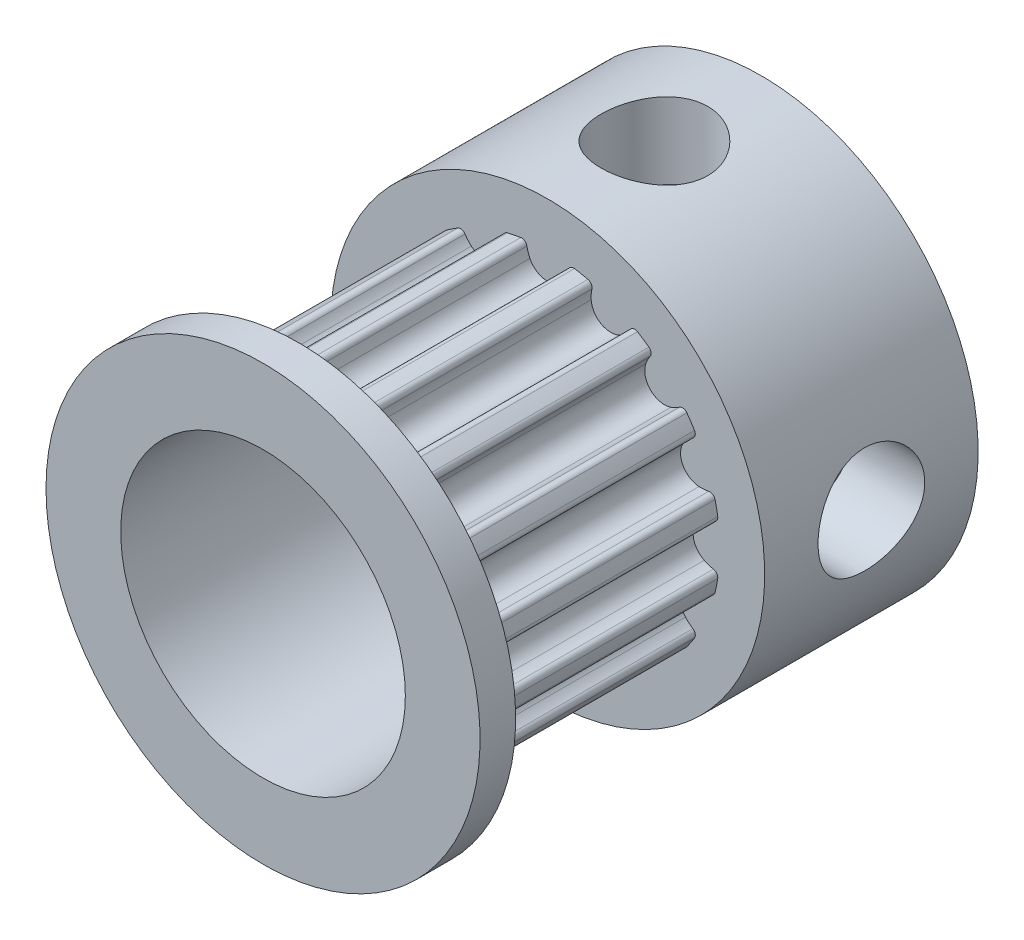
SolidWorks part; units mm, degrees
material "6061 Alloy"
ref_plane "Front Plane" through (0, 0, 0) normal (0, 0, 1) x (1, 0, 0)
ref_plane "Top Plane" through (0, 0, 0) normal (0, 1, 0) x (1, 0, 0)
ref_plane "Right Plane" through (0, 0, 0) normal (1, 0, 0) x (0, 0, -1)
sketch "Sketch1" plane through (0, 0, 0) normal (0, 0, 1) x (1, 0, 0)
  line L0 (0, 0) -> (0, 5.093) construction
  circle A0 centre (0, 0) radius 5.093 construction
  circle A1 centre (0, 0) radius 4.839
  dimension "D1" = 10.1859
  dimension "D2" = 0.254
extrude "Boss-Extrude1" add sketch "Sketch1" along normal mid plane 7 contours A1
sketch "Sketch2" plane through (0, 0, 3.5) normal (0, 0, 1) x (1, 0, 0)
  line L0 (0, 0) -> (0, 4.839) construction
  line L1 (0, 4.839) -> (0.4, 4.839) construction
  line L2 (0, 0) -> (0.944, 4.746) construction
  line L3 (0, 0) -> (-0.944, 4.746) construction
  line L4 (-0.944, 4.746) -> (-0.944, 5.246)
  line L5 (-0.944, 5.246) -> (0.944, 5.246)
  line L6 (0.944, 5.246) -> (0.944, 4.746)
  circle A0 centre (0, 0) radius 4.839 construction
  circle A1 centre (0.4, 4.839) radius 1 construction
  circle A2 centre (0, 4.644) radius 0.555 construction
  circle A3 centre (-0.7312, 4.6316) radius 0.15 construction
  circle A4 centre (0, 0) radius 4.839 construction
  arc A5 (-0.7545, 4.7798) -> (-0.5836, 4.6586) centre (-0.7312, 4.6316) cw
  arc A6 (-0.5836, 4.6586) -> (-0.4989, 4.4008) centre (0.4, 4.839) ccw
  arc A7 (-0.4989, 4.4008) -> (0.4989, 4.4008) centre (0, 4.644) ccw
  arc A8 (-0.944, 4.746) -> (-0.7545, 4.7798) centre (0, 0) cw
  arc A9 (0.5836, 4.6586) -> (0.4989, 4.4008) centre (-0.4, 4.839) cw
  arc A10 (0.7545, 4.7798) -> (0.5836, 4.6586) centre (0.7312, 4.6316) ccw
  arc A11 (0.7545, 4.7798) -> (0.944, 4.746) centre (0, 0) cw
  dimension "D4" = 2
  dimension "D5" = 1.11
  dimension "D6" = 0.3
  dimension "D1" = 0.4
  dimension "D2" = 11.25
  dimension "D3" = 11.25
  dimension "D7" = 0.5
extrude "Cut-Extrude1" cut sketch "Sketch2" against normal through all both and the other way through all
pattern_circular "CirPattern1" count 16 over 360 about axis through (0, 0, 0) along (0, 0, 1) of "Cut-Extrude1"
sketch "Sketch3" plane through (0, 0, -3.5) normal (0, 0, -1) x (-1, 0, 0)
  circle A0 centre (0, 0) radius 6.1
  dimension "D1" = 12.2
extrude "Boss-Extrude2" add sketch "Sketch3" along normal blind 6
sketch "Sketch4" plane through (0, 0, 3.5) normal (0, 0, 1) x (1, 0, 0)
  circle A0 centre (0, 0) radius 6.1
  circle A1 centre (0, 0) radius 6.1 construction
extrude "Boss-Extrude3" add sketch "Sketch4" along normal blind 1
sketch "Sketch5" plane through (0, 0, 4.5) normal (0, 0, 1) x (1, 0, 0)
  circle A0 centre (0, 0) radius 4
  dimension "D1" = 8
extrude "Cut-Extrude2" cut sketch "Sketch5" against normal through all
sketch "Sketch6" plane through (0, 0, 0) normal (1, 0, 0) x (0, 0, -1)
  line L0 (3.5, 0) -> (9.5, 0) construction
  line L1 (3.5, 0.4989) -> (3.5, -0.4989) construction
  line L2 (9.5, -6.1) -> (9.5, 6.1) construction
  circle A0 centre (6.5, 0) radius 1.5
  dimension "D1" = 3
extrude "Cut-Extrude3" cut sketch "Sketch6" along normal through all
pattern_circular "CirPattern2" count 2 over 90 about axis through (0, 0, -9.5) along (0, 0, 1) of "Cut-Extrude3"
